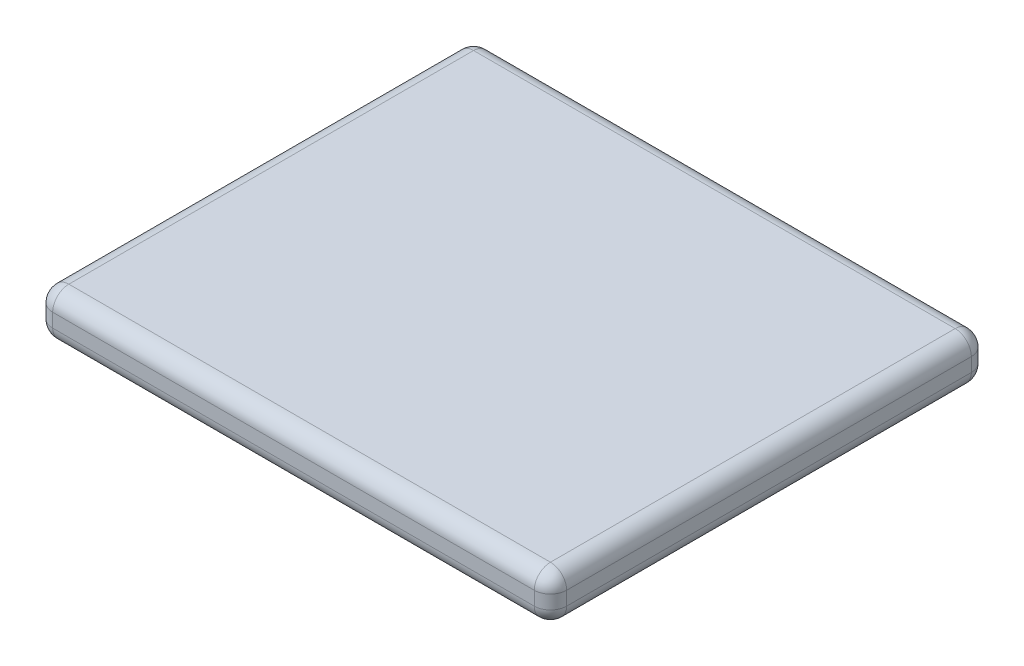
SolidWorks part; units mm, degrees
ref_plane "Front Plane" through (0, 0, 0) normal (0, 0, 1) x (1, 0, 0)
ref_plane "Top Plane" through (0, 0, 0) normal (0, 1, 0) x (1, 0, 0)
ref_plane "Right Plane" through (0, 0, 0) normal (1, 0, 0) x (0, 0, -1)
sketch "Sketch1" plane through (0, 0, 0) normal (0, 1, 0) x (1, 0, 0)
  line L1 (0, 0) -> (63.5, 0)
  line L2 (0, 0) -> (0, 54)
  line L3 (0, 54) -> (63.5, 54)
  line L4 (63.5, 0) -> (63.5, 54)
extrude "Boss-Extrude1" add sketch "Sketch1" along normal blind 5.7
fillet "Fillet1" radius 2 12 edges at (0, 0, -27) (31.75, 0, -54) (31.75, 5.7, -54) (0, 2.85, -54) (63.5, 2.85, -54) (63.5, 0, -27) (63.5, 5.7, -27) (63.5, 2.85, 0) (0, 5.7, -27) (0, 2.85, 0) (31.75, 0, 0) (31.75, 5.7, 0)
